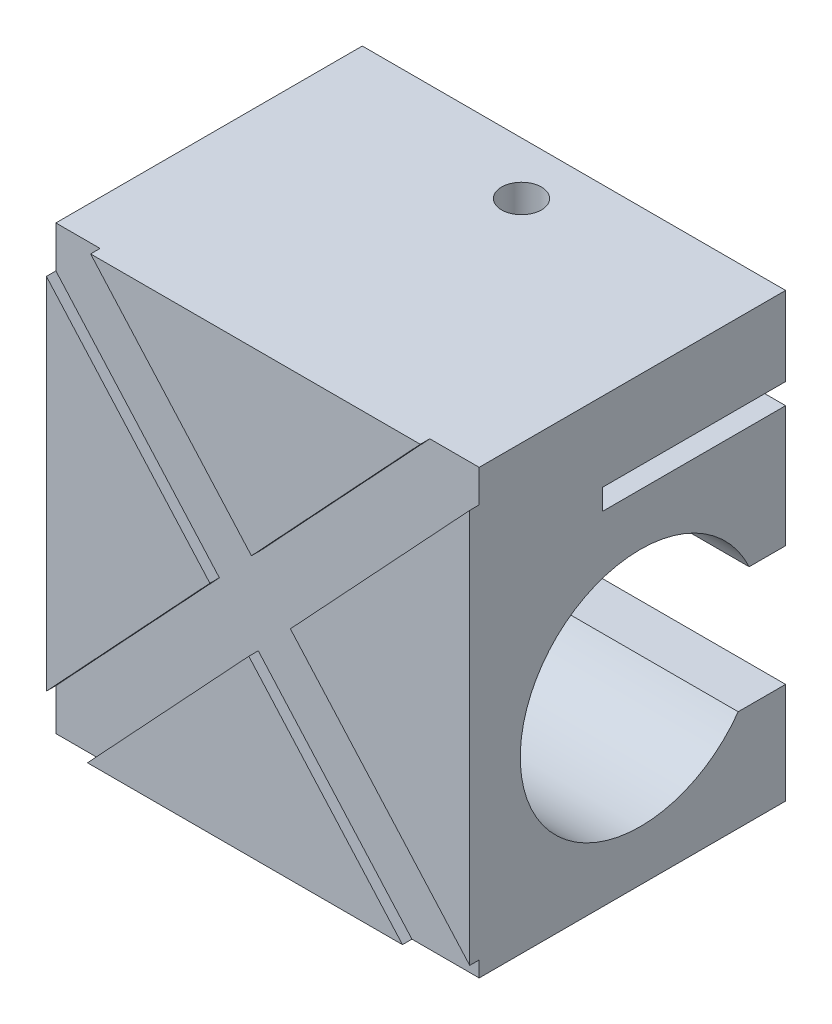
SolidWorks part; units mm, degrees
material "AISI 1020"
ref_plane "Front Plane" through (0, 0, 0) normal (0, 0, 1) x (1, 0, 0)
ref_plane "Top Plane" through (0, 0, 0) normal (0, 1, 0) x (1, 0, 0)
ref_plane "Right Plane" through (0, 0, 0) normal (1, 0, 0) x (0, 0, -1)
sketch "Sketch1" plane through (0, 0, 0) normal (0, 1, 0) x (1, 0, 0)
  line L1 (0, 0) -> (67, 0)
  line L2 (0, 0) -> (0, -50)
  line L3 (0, -50) -> (67, -50)
  line L4 (67, 0) -> (67, -50)
  dimension "D1" = 50
  dimension "D2" = 67
extrude "Boss-Extrude1" add sketch "Sketch1" along normal blind 70
sketch "Sketch2" plane through (67, 0, 0) normal (1, 0, 0) x (0, 0, -1)
  line L0 (-50, 70) -> (-50, 0) construction
  line L1 (-50, 0) -> (0, 0) construction
  circle A0 centre (-23, 27) radius 19
  point P4 (0, 0)
  point P6 (-24.5108, 37.8741)
  dimension "D1" = 38
  dimension "D2" = 27
  dimension "D3" = 27
extrude "Cut-Extrude1" cut sketch "Sketch2" against normal blind 70 contours A0
sketch "Sketch3" plane through (67, 0, 0) normal (1, 0, 0) x (0, 0, -1)
  line L1 (0, 70) -> (0, 0) construction
  line L2 (0, 25.5) -> (0, 35)
  line L3 (0, 35) -> (-5.7663, 35)
  line L4 (-5.7663, 35) -> (-4, 27)
  line L5 (0, 25.5) -> (0, 16)
  line L6 (0, 16) -> (-7.5063, 16.0025)
  line L7 (-7.5063, 16.0025) -> (-4, 27)
  circle A0 centre (-23, 27) radius 19 construction
  point P7 (0, 0)
  point P12 (0, 16.9021)
  point P13 (0, 0)
  point P14 (-7.5063, 16)
  dimension "D1" = 9.5
  dimension "D2" = 9.5
extrude "Cut-Extrude2" cut sketch "Sketch3" against normal blind 70
sketch "Sketch4" plane through (67, 0, 0) normal (1, 0, 0) x (0, 0, -1)
  line L0 (0, 70) -> (0, 35) construction
  line L1 (0, 57.5) -> (-29, 57.5)
  line L2 (0, 57.5) -> (0, 54.2)
  line L3 (0, 54.2) -> (-29, 54.2)
  line L4 (-29, 57.5) -> (-29, 54.2)
  line L5 (-50, 70) -> (0, 70) construction
  dimension "D1" = 12.5
  dimension "D2" = 29
  dimension "D3" = 3.3
extrude "Cut-Extrude3" cut sketch "Sketch4" against normal blind 70
sketch "Sketch5" plane through (0, 70, 0) normal (0, 1, 0) x (1, 0, 0)
  line L0 (0, 0) -> (0, -50) construction
  line L1 (67, 0) -> (0, 0) construction
  circle A0 centre (33.5, -8.3) radius 3.15
  dimension "D3" = 6.3
  dimension "D1" = 33.5
  dimension "D2" = 8.3
extrude "Cut-Extrude4" cut sketch "Sketch5" against normal up to surface (12.5 mm away) up to face at (33.5, 57.5, 14.5)
sketch "Sketch6" plane through (0, 0, 50) normal (0, 0, 1) x (1, 0, 0)
  line L0 (0, 63.425) -> (56.3592, 0)
  line L1 (0, 70) -> (0, 0) construction
  line L2 (0, 0) -> (67, 0) construction
  line L3 (56.3592, 0) -> (67, 0)
  line L4 (67, 0) -> (67, 2.4777)
  line L5 (67, 70) -> (67, 0) construction
  line L6 (67, 2.4777) -> (7, 70)
  line L7 (0, 70) -> (67, 70) construction
  line L8 (7, 70) -> (0, 70)
  line L9 (0, 70) -> (0, 63.425)
  dimension "D1" = 9.6
  dimension "D2" = 7
extrude "Cut-Extrude6" cut sketch "Sketch6" against normal blind 1.5
sketch "Sketch7" plane through (0, 0, 50) normal (0, 0, 1) x (1, 0, 0)
  line L0 (0, 6.5649) -> (59.1797, 70)
  line L1 (0, 63.425) -> (0, 0) construction
  line L2 (7, 70) -> (67, 70) construction
  line L3 (59.1797, 70) -> (67, 70)
  line L4 (67, 70) -> (67, 64.8485)
  line L5 (67, 70) -> (67, 2.4777) construction
  line L6 (67, 64.8485) -> (6.5017, 0)
  line L7 (0, 0) -> (56.3592, 0) construction
  line L8 (6.5017, 0) -> (0, 0)
  line L9 (0, 0) -> (0, 6.5649)
extrude "Cut-Extrude7" cut sketch "Sketch7" against normal blind 1.5
